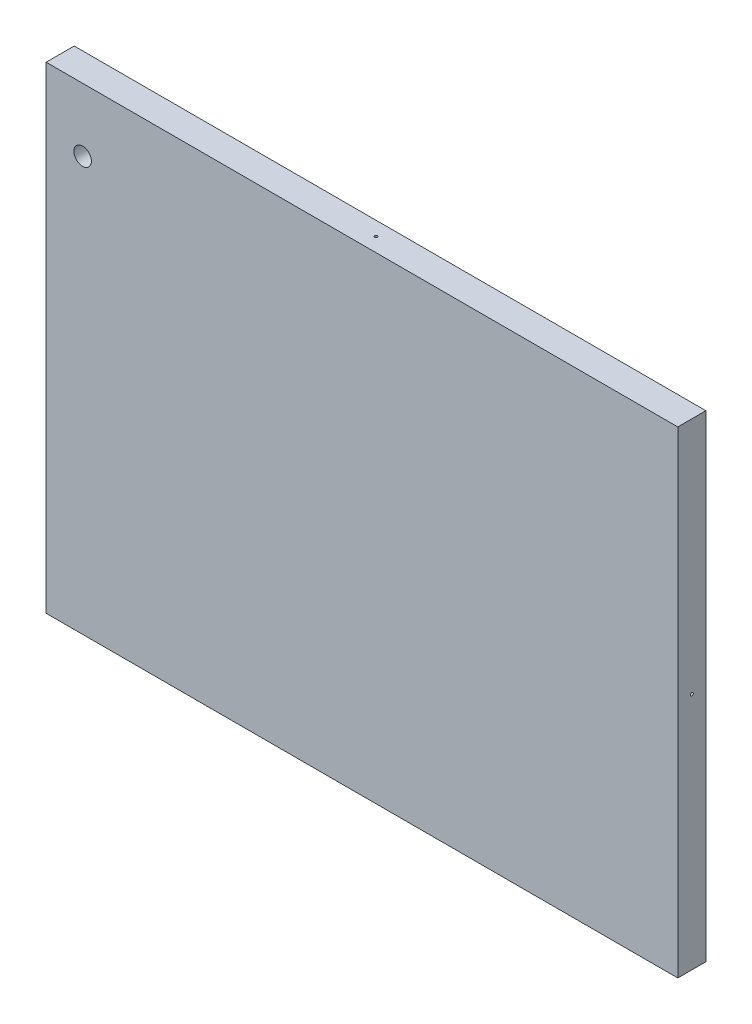
SolidWorks part; units mm, degrees
material "1.4511 (X3CrNb17)"
ref_plane "前视基准面" through (0, 0, 0) normal (0, 0, 1) x (1, 0, 0)
ref_plane "上视基准面" through (0, 0, 0) normal (0, 1, 0) x (1, 0, 0)
ref_plane "右视基准面" through (0, 0, 0) normal (1, 0, 0) x (0, 0, -1)
sketch "草图2" plane through (0, 0, 0) normal (0, 0, 1) x (1, 0, 0)
  line L1 (-450, 340) -> (450, 340)
  line L2 (-450, 340) -> (-450, -340)
  line L3 (-450, -340) -> (450, -340)
  line L4 (450, 340) -> (450, -340)
  line L5 (-450, 340) -> (450, -340) construction
  line L6 (-450, -340) -> (450, 340) construction
  point P0 (0, 0)
  dimension "D1" = 900
  dimension "D2" = 680
extrude "凸台-拉伸1" add sketch "草图2" along normal blind 40
sketch "草图3" plane through (0, -340, 0) normal (0, -1, 0) x (1, 0, 0)
  line L0 (-450, 40) -> (-450, 0) construction
  point P0 (0, 20)
  dimension "D1" = 450
hole_wizard "M5 螺纹孔1" positions "草图4" profile "草图5" tap size "M5" standard "GB" end condition through all
sketch "草图4" plane through (0, -340, 0) normal (0, -1, 0) x (-1, 0, 0)
  point P0 (0, -20)
sketch "草图5" plane through (0, -340, 20) normal (1, 0, 0) x (0, 0, -1)
  line L0 (0, 0) -> (0, 680)
  line L1 (0, 680) -> (2.1, 680)
  line L2 (2.1, 680) -> (2.1, 0)
  line L5 (2.1, 0) -> (0, 0)
  line L11 (0, -6.35) -> (0, 107.95) construction
  dimension "通孔螺纹孔钻头直径" = 4.2
  dimension "通孔螺纹孔钻头深度" = 680
cosmetic thread "孔螺蚊线1" parameters "D2"=5
sketch "草图6" plane through (-450, 0, 0) normal (-1, 0, 0) x (0, 0, 1)
  line L0 (40, 340) -> (0, 340) construction
  point P0 (20, 0)
  dimension "D1" = 340
hole_wizard "M5 螺纹孔2" positions "草图7" profile "草图8" tap size "M5" standard "GB" end condition through all
sketch "草图7" plane through (-450, 0, 0) normal (-1, 0, 0) x (0, 0, 1)
  point P0 (20, 0)
sketch "草图8" plane through (-450, 0, 20) normal (0, 1, 0) x (0, 0, 1)
  line L0 (0, 0) -> (0, 900)
  line L1 (0, 900) -> (2.1, 900)
  line L2 (2.1, 900) -> (2.1, 0)
  line L5 (2.1, 0) -> (0, 0)
  line L11 (0, -6.35) -> (0, 107.95) construction
  dimension "通孔螺纹孔钻头直径" = 4.2
  dimension "通孔螺纹孔钻头深度" = 900
cosmetic thread "孔螺蚊线2" parameters "D2"=5
sketch "草图9" plane through (0, 0, 40) normal (0, 0, 1) x (1, 0, 0)
  line L0 (450, 340) -> (-450, 340) construction
  line L1 (-450, 340) -> (-450, -340) construction
  circle A0 centre (-398, 250) radius 12.5
  dimension "D1" = 25
  dimension "D2" = 90
  dimension "D3" = 52
extrude "切除-拉伸1" cut sketch "草图9" against normal through all
